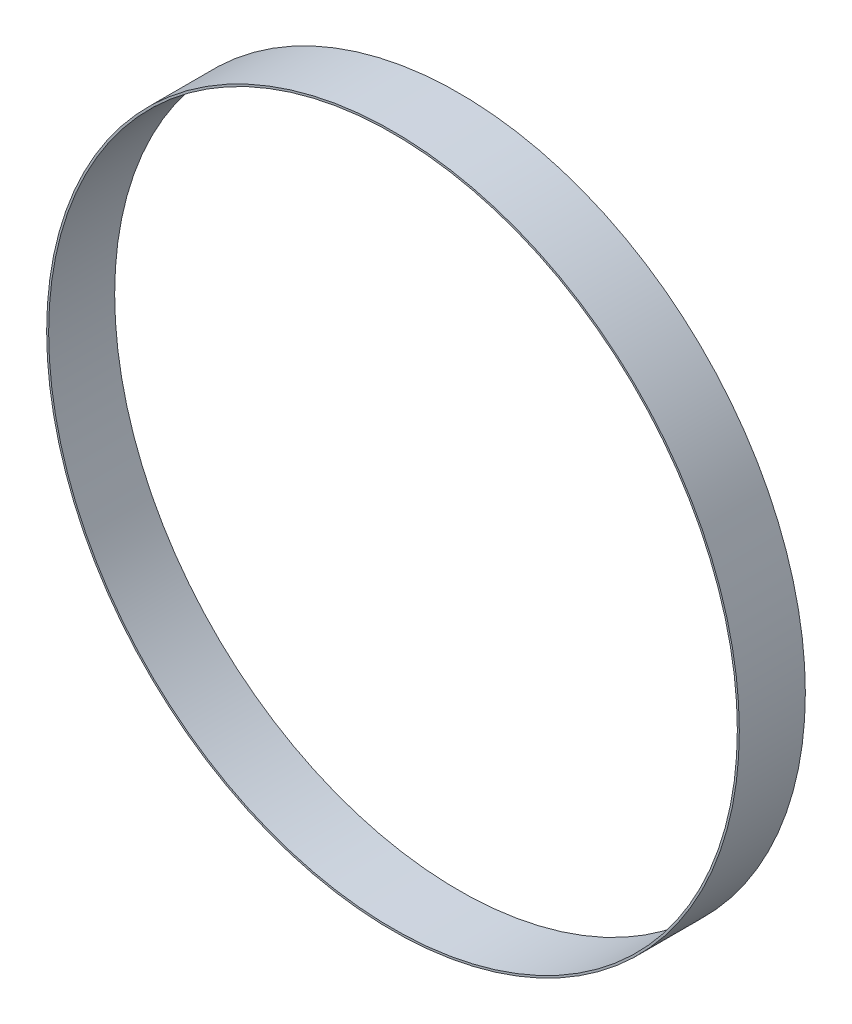
SolidWorks part; units mm, degrees
material "Ti-8Al-1Mo-1V annealed sheet (SS)"
ref_plane "Front Plane" through (0, 0, 0) normal (0, 0, 1) x (1, 0, 0)
ref_plane "Top Plane" through (0, 0, 0) normal (0, 1, 0) x (1, 0, 0)
ref_plane "Right Plane" through (0, 0, 0) normal (1, 0, 0) x (0, 0, -1)
sketch "Sketch1" plane through (0, 0, 0) normal (0, 0, 1) x (1, 0, 0)
  circle A0 centre (0, 0) radius 521.5
  circle A1 centre (0, 0) radius 524.5
extrude "Boss-Extrude1" add sketch "Sketch1" along normal blind 100
